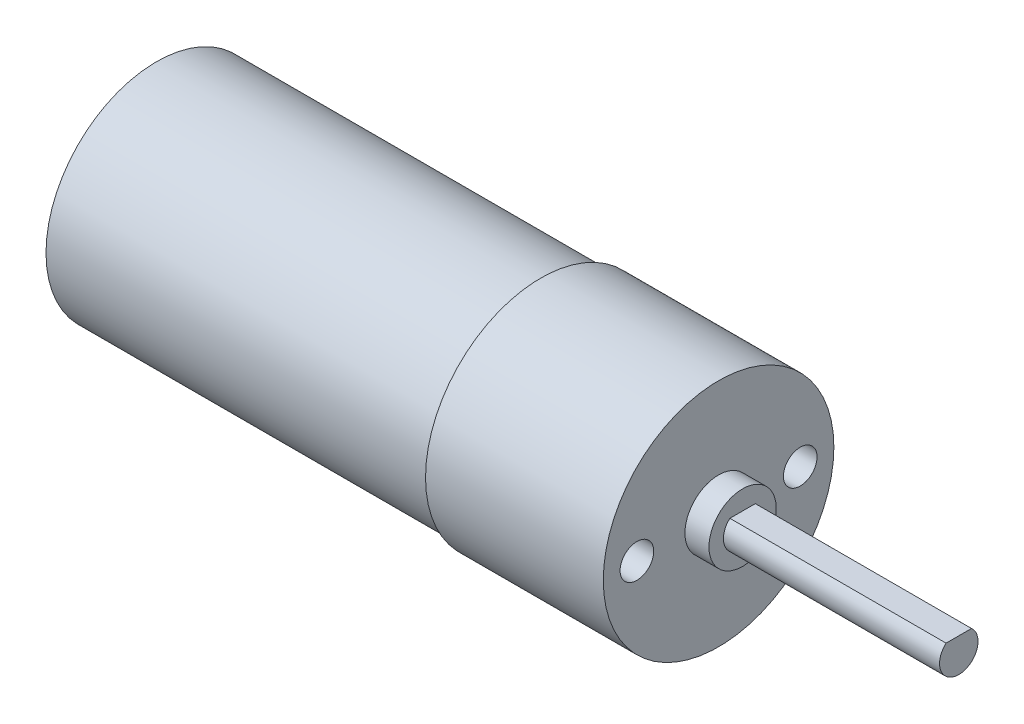
SolidWorks part; units mm, degrees
ref_plane "Front Plane" through (0, 0, 0) normal (0, 0, 1) x (1, 0, 0)
ref_plane "Top Plane" through (0, 0, 0) normal (0, 1, 0) x (1, 0, 0)
ref_plane "Right Plane" through (0, 0, 0) normal (1, 0, 0) x (0, 0, -1)
sketch "Sketch1" plane through (0, 0, 0) normal (0, 1, 0) x (1, 0, 0)
  line L1 (-25, 12) -> (-83.5, 12)
  line L2 (-83.5, 12) -> (-83.5, 0)
  line L3 (-83.5, 0) -> (0, 0)
  line L4 (0, 0) -> (0, 2)
  line L5 (0, 2) -> (-22.5, 2)
  line L6 (-22.5, 2) -> (-22.5, 3.5)
  line L7 (-22.5, 3.5) -> (-25, 3.5)
  line L8 (-25, 3.5) -> (-25, 12)
  dimension "D1" = 3.5
  dimension "D2" = 12
  dimension "D3" = 58.5
  dimension "D4" = 25
  dimension "D5" = 2.5
  dimension "D6" = 2
revolve "Revolve1" add sketch "Sketch1" angle 360 about L3
sketch "Sketch2" plane through (0, 0, 0) normal (1, 0, 0) x (0, 0, -1)
  line L0 (1.3229, 1.5) -> (-1.3229, 1.5)
  arc A0 (1.3229, 1.5) -> (-1.3229, 1.5) centre (0, 0) ccw
  circle A1 centre (0, 0) radius 2 construction
  point P7 (0, -2)
  dimension "D1" = 3.5
extrude "Cut-Extrude1" cut sketch "Sketch2" against normal up to surface (22.5 mm away) up to face at (-22.5, 0, 3.5)
sketch "Sketch4" plane through (-25, 0, 0) normal (1, 0, 0) x (0, 0, -1)
  line L0 (0, 0) -> (-8.5, 0) construction
  circle A0 centre (-8.5, 0) radius 1.75
  circle A1 centre (8.5, 0) radius 1.75
  point P8 (0, 0)
  dimension "D2" = 3.5
  dimension "D1" = 8.5
  dimension "D3" = 2
extrude "Cut-Extrude2" cut sketch "Sketch4" against normal blind 5
sketch "Sketch5" plane through (-83.5, 0, 0) normal (-1, 0, 0) x (0, 0, 1)
  circle A0 centre (0, 0) radius 12
  circle A1 centre (0, 0) radius 12 construction
  circle A2 centre (0, 0) radius 11.5
  dimension "D1" = 0.5
extrude "Cut-Extrude3" cut sketch "Sketch5" against normal blind 40
